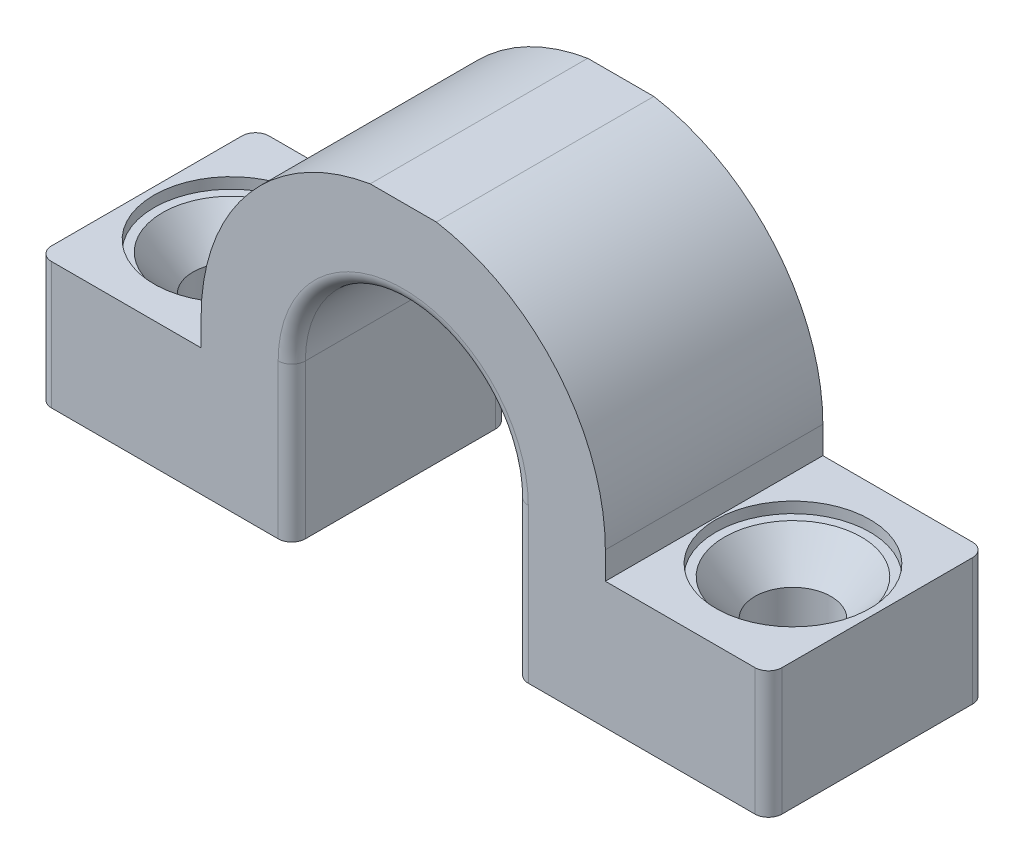
SolidWorks part; units mm, degrees
ref_plane "Front Plane" through (0, 0, 0) normal (0, 0, 1) x (1, 0, 0)
ref_plane "Top Plane" through (0, 0, 0) normal (0, 1, 0) x (1, 0, 0)
ref_plane "Right Plane" through (0, 0, 0) normal (1, 0, 0) x (0, 0, -1)
sketch "Sketch1" plane through (0, 0, 0) normal (0, 0, 1) x (1, 0, 0)
  line L0 (-11.15, 0) -> (-11.15, -1.5)
  line L1 (-11.15, -1.5) -> (-20.15, -1.5)
  line L2 (-20.15, -1.5) -> (-20.15, -8.5)
  line L3 (-20.15, -8.5) -> (-6.15, -8.5)
  line L4 (-6.15, -8.5) -> (-6.15, 0)
  line L5 (6.15, 0) -> (6.15, -8.5)
  line L6 (6.15, -8.5) -> (20.15, -8.5)
  line L7 (20.15, -8.5) -> (20.15, -1.5)
  line L8 (20.15, -1.5) -> (11.15, -1.5)
  line L9 (11.15, -1.5) -> (11.15, 0)
  arc A0 (6.15, 0) -> (-6.15, 0) centre (0, 0) ccw
  arc A1 (11.15, 0) -> (-11.15, 0) centre (0, 0) ccw
  dimension "D1" = 12.3
  dimension "D2" = 5
  dimension "D3" = 7
  dimension "D4" = 14
  dimension "D5" = 8.5
extrude "Boss-Extrude1" add sketch "Sketch1" along normal blind 12
sketch "Sketch4" plane through (0, -1.5, 0) normal (0, 1, 0) x (1, 0, 0)
  line L0 (-11.15, 0) -> (-20.15, 0) construction
  line L1 (-20.15, -12) -> (-20.15, 0) construction
  line L2 (20.15, 0) -> (11.15, 0) construction
  line L3 (20.15, -12) -> (20.15, 0) construction
  circle A0 centre (-15.5, -6) radius 2.1
  circle A1 centre (15.5, -6) radius 2.1
  point P4 (-15.65, 0)
  point P7 (-20.15, -6)
  point P12 (15.65, 0)
  point P15 (20.15, -6)
  point P16 (-14.8345, -6)
  point P17 (14.0945, -6)
  dimension "D1" = 4.2
  dimension "D2" = 0.15
  dimension "D3" = 0.15
extrude "Cut-Extrude1" cut sketch "Sketch4" against normal through all
ref_plane "Plane1" through (0, 11, 0) normal (0, 1, 0) x (1, 0, 0)
sketch "Sketch5" plane through (0, 11, 0) normal (0, 1, 0) x (1, 0, 0)
  line L1 (-8.3673, 1.4476) -> (8.7588, 1.4476)
  line L2 (-8.3673, 1.4476) -> (-8.3673, -13.0362)
  line L3 (-8.3673, -13.0362) -> (8.7588, -13.0362)
  line L4 (8.7588, 1.4476) -> (8.7588, -13.0362)
  line L5 (-8.3673, 1.4476) -> (8.7588, -13.0362) construction
  line L6 (-8.3673, -13.0362) -> (8.7588, 1.4476) construction
  point P0 (0.1957, -5.7943)
extrude "Cut-Extrude2" cut sketch "Sketch5" along normal through all
fillet "Fillet2" radius 0.75 10 edges at (20.15, -5, 0) (20.15, -5, 12) (-20.15, -5, 0) (-20.15, -5, 12) (-6.15, -4.25, 0) (0, 6.15, 0) (6.15, -4.25, 12) (0, 6.15, 12) (6.15, -4.25, 0) (-6.15, -4.25, 12)
sketch "Sketch7" plane through (0, -1.5, 0) normal (0, 1, 0) x (1, 0, 0)
  circle A0 centre (-15.5, -6) radius 4.25
  circle A1 centre (15.5, -6) radius 4.25
  dimension "D1" = 8.5
extrude "Cut-Extrude4" cut sketch "Sketch7" against normal blind 0.6
chamfer "Chamfer1" distance 2 angle 40 2 edges at (13.4, -2.1, 6) (-17.6, -2.1, 6)
